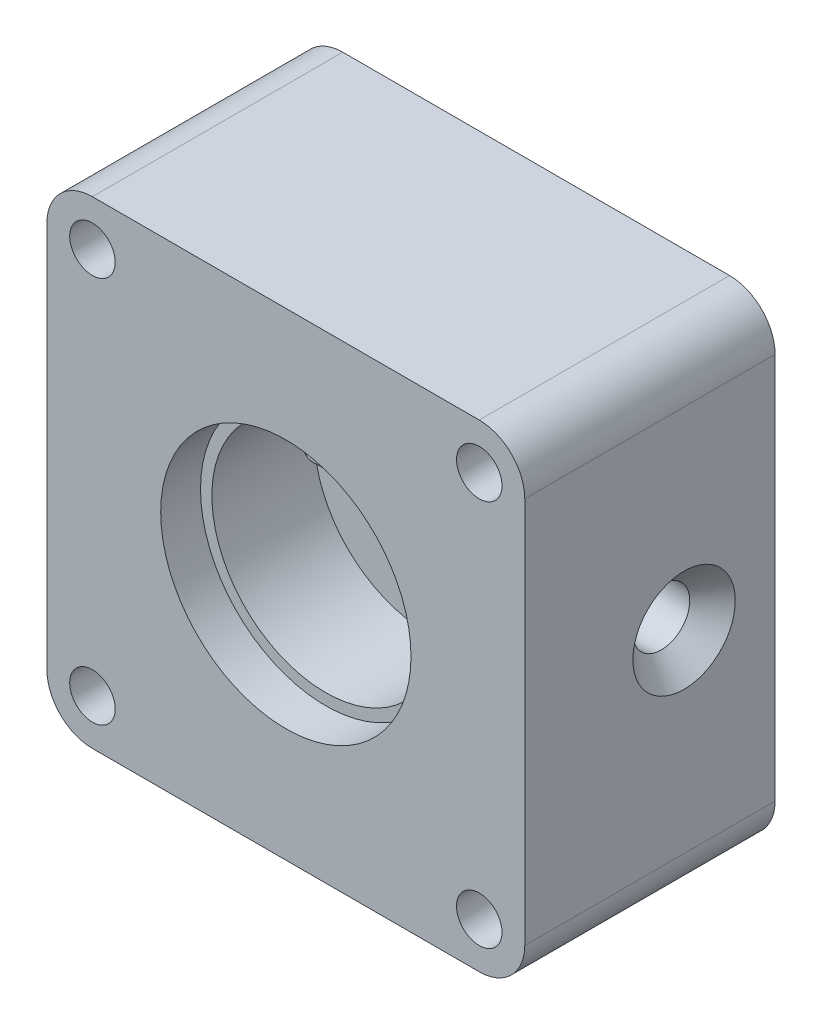
SolidWorks part; units mm, degrees
ref_plane "Alzado" through (0, 0, 0) normal (0, 0, 1) x (1, 0, 0)
ref_plane "Planta" through (0, 0, 0) normal (0, 1, 0) x (1, 0, 0)
ref_plane "Vista lateral" through (0, 0, 0) normal (1, 0, 0) x (0, 0, -1)
sketch "Croquis1" plane through (0, 0, 0) normal (0, 0, 1) x (1, 0, 0)
  line L1 (-21, 21) -> (21, 21)
  line L2 (-21, 21) -> (-21, -21)
  line L3 (-21, -21) -> (21, -21)
  line L4 (21, 21) -> (21, -21)
  line L5 (-21, 21) -> (21, -21) construction
  line L6 (-21, -21) -> (21, 21) construction
  point P0 (0, 0)
  dimension "D1" = 42
  dimension "D2" = 42
extrude "Saliente-Extruir1" add sketch "Croquis1" along normal blind 22
sketch "Croquis2" plane through (0, 0, 0) normal (0, 0, -1) x (-1, 0, 0)
  line L0 (-11.3, 11.3) -> (-11.3, -11.3)
  line L1 (12.5, 12.5) -> (-12.5, 12.5)
  line L2 (12.5, 12.5) -> (12.5, -12.5)
  line L3 (12.5, -12.5) -> (-12.5, -12.5)
  line L4 (-12.5, 12.5) -> (-12.5, -12.5)
  line L5 (12.5, 12.5) -> (-12.5, -12.5) construction
  line L6 (12.5, -12.5) -> (-12.5, 12.5) construction
  line L7 (11.3, -11.3) -> (-11.3, -11.3)
  line L8 (11.3, 11.3) -> (11.3, -11.3)
  line L9 (11.3, 11.3) -> (-11.3, 11.3)
  point P0 (0, 0)
  dimension "D1" = 25
  dimension "D2" = 25
  dimension "D3" = 1.2
extrude "Cortar-Extruir1" cut sketch "Croquis2" against normal blind 15
sketch "Croquis3" plane through (0, 0, 22) normal (0, 0, 1) x (1, 0, 0)
  circle A0 centre (0, 0) radius 5
  dimension "D1" = 10
extrude "Cortar-Extruir2" cut sketch "Croquis3" against normal through all
sketch "Croquis4" plane through (0, 0, 22) normal (0, 0, 1) x (1, 0, 0)
  circle A0 centre (0, 0) radius 11
  dimension "D1" = 22
extrude "Cortar-Extruir3" cut sketch "Croquis4" against normal blind 3.5
sketch "Croquis5" plane through (0, 0, 18.5) normal (0, 0, 1) x (1, 0, 0)
  circle A0 centre (0, 0) radius 10
  dimension "D1" = 20
extrude "Cortar-Extruir4" cut sketch "Croquis5" against normal blind 9
sketch "Croquis6" plane through (0, 0, 0) normal (0, 0, -1) x (-1, 0, 0)
  line L1 (-17, 17) -> (17, 17) construction
  line L2 (-17, 17) -> (-17, -17) construction
  line L3 (-17, -17) -> (17, -17) construction
  line L4 (17, 17) -> (17, -17) construction
  line L5 (-17, 17) -> (17, -17) construction
  line L6 (-17, -17) -> (17, 17) construction
  circle A0 centre (17, 17) radius 2
  circle A1 centre (-17, 17) radius 2
  circle A2 centre (-17, -17) radius 2
  circle A3 centre (17, -17) radius 2
  point P0 (0, 0)
  dimension "D3" = 4
  dimension "D4" = 4
  dimension "D5" = 4
  dimension "D6" = 4
  dimension "D1" = 34
  dimension "D2" = 34
extrude "Cortar-Extruir5" cut sketch "Croquis6" against normal through all
fillet "Redondeo1" radius 4 4 edges at (21, -21, 11) (-21, -21, 11) (-21, 21, 11) (21, 21, 11)
sketch "Croquis7" plane through (21, 0, 0) normal (1, 0, 0) x (0, 0, -1)
  line L0 (0, 0) -> (-22, 0) construction
  line L1 (0, -17) -> (0, 17) construction
  line L2 (-22, -17) -> (-22, 17) construction
  circle A0 centre (-8, 0) radius 2.5
  dimension "D1" = 5
  dimension "D2" = 8
extrude "Cortar-Extruir7" cut sketch "Croquis7" against normal through all
chamfer "Chaflán1" distance 2 angle 45 2 edges at (-21, 2.5, 8) (21, 2.5, 8)
sketch "Croquis8" plane through (0, -21, 0) normal (0, -1, 0) x (1, 0, 0)
  line L0 (-17, 6.4947) -> (17, 6.4947) construction
  line L1 (-17, 22) -> (-17, 0) construction
  line L2 (17, 0) -> (17, 22) construction
  text T0 "FRONT" font "Arial" height 4
